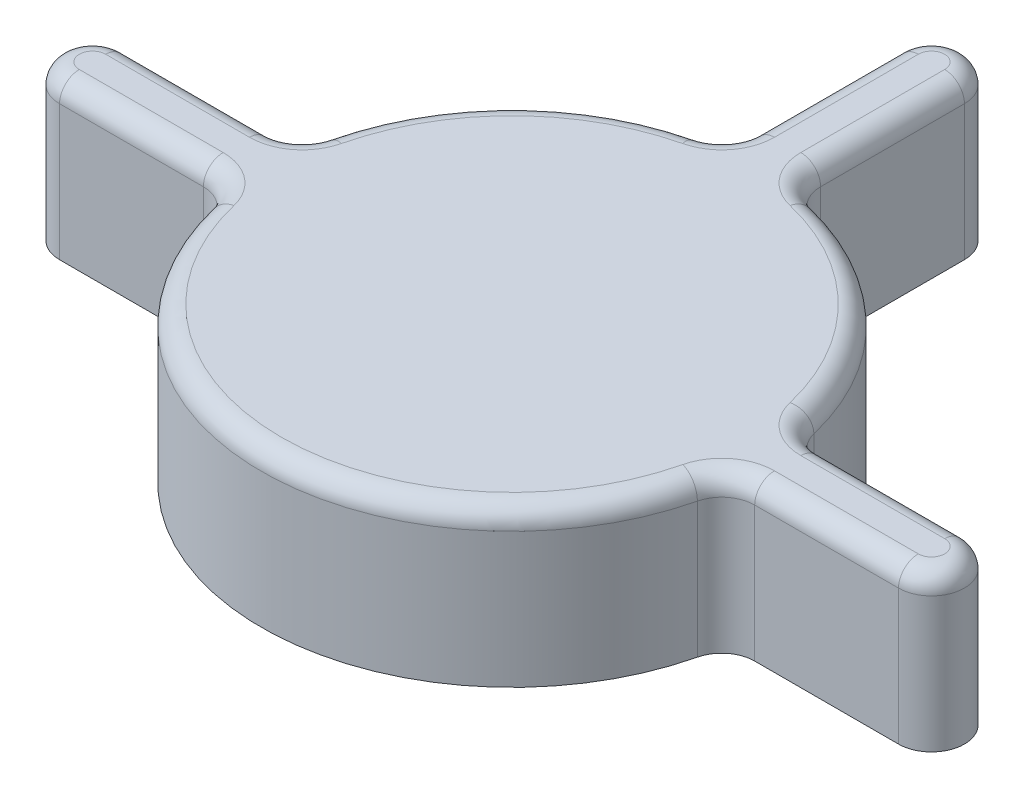
SolidWorks part; units mm, degrees
material "ABS PC"
ref_plane "Plan de face" through (0, 0, 0) normal (0, 0, 1) x (1, 0, 0)
ref_plane "Plan de dessus" through (0, 0, 0) normal (0, 1, 0) x (1, 0, 0)
ref_plane "Plan de droite" through (0, 0, 0) normal (1, 0, 0) x (0, 0, -1)
sketch "Esquisse1" plane through (0, 0, 0) normal (0, 1, 0) x (1, 0, 0)
  line L8 (15.5, -48.7904) -> (15.5, -37.7988)
  line L9 (41.821, -5) -> (63.6396, -5)
  line L10 (63.6396, 5) -> (41.821, 5)
  line L11 (5, 41.821) -> (5, 63.6396)
  line L12 (-5, 63.6396) -> (-5, 41.821)
  line L13 (-41.821, 5) -> (-63.6396, 5)
  line L14 (-63.6396, -5) -> (-41.821, -5)
  line L15 (-15.5, -37.7988) -> (-15.5, -48.7904)
  line L17 (41.821, -5) -> (63.6396, -5)
  line L18 (63.6396, 5) -> (41.821, 5)
  line L19 (5, 41.821) -> (5, 63.6396)
  line L20 (-5, 63.6396) -> (-5, 41.821)
  line L21 (-41.821, 5) -> (-63.6396, 5)
  line L22 (-63.6396, -5) -> (-41.821, -5)
  arc A16 (18.1163, -33.4036) -> (15.5, -37.7988) centre (20.5, -37.7988) ccw
  arc A17 (18.1163, -33.4036) -> (36.9581, -8.8372) centre (0, 0) ccw
  arc A18 (41.821, -5) -> (36.9581, -8.8372) centre (41.821, -10) ccw
  arc A19 (63.6396, -5) -> (63.6396, 5) centre (63.6396, 0) ccw
  arc A20 (36.9581, 8.8372) -> (41.821, 5) centre (41.821, 10) ccw
  arc A21 (36.9581, 8.8372) -> (8.8372, 36.9581) centre (0, 0) ccw
  arc A22 (5, 41.821) -> (8.8372, 36.9581) centre (10, 41.821) ccw
  arc A23 (5, 63.6396) -> (-5, 63.6396) centre (0, 63.6396) ccw
  arc A24 (-8.8372, 36.9581) -> (-5, 41.821) centre (-10, 41.821) ccw
  arc A25 (-8.8372, 36.9581) -> (-36.9581, 8.8372) centre (0, 0) ccw
  arc A26 (-41.821, 5) -> (-36.9581, 8.8372) centre (-41.821, 10) ccw
  arc A27 (-63.6396, 5) -> (-63.6396, -5) centre (-63.6396, 0) ccw
  arc A28 (-36.9581, -8.8372) -> (-41.821, -5) centre (-41.821, -10) ccw
  arc A29 (-36.9581, -8.8372) -> (-18.1163, -33.4036) centre (0, 0) ccw
  arc A30 (-15.5, -37.7988) -> (-18.1163, -33.4036) centre (-20.5, -37.7988) ccw
  arc A31 (-15.5, -48.7904) -> (15.5, -48.7904) centre (0, -48.7904) ccw
  arc A33 (-18.1163, -33.4036) -> (36.9581, -8.8372) centre (0, 0) ccw
  arc A34 (41.821, -5) -> (36.9581, -8.8372) centre (41.821, -10) ccw
  arc A35 (63.6396, -5) -> (63.6396, 5) centre (63.6396, 0) ccw
  arc A36 (36.9581, 8.8372) -> (41.821, 5) centre (41.821, 10) ccw
  arc A37 (36.9581, 8.8372) -> (8.8372, 36.9581) centre (0, 0) ccw
  arc A38 (5, 41.821) -> (8.8372, 36.9581) centre (10, 41.821) ccw
  arc A39 (5, 63.6396) -> (-5, 63.6396) centre (0, 63.6396) ccw
  arc A40 (-8.8372, 36.9581) -> (-5, 41.821) centre (-10, 41.821) ccw
  arc A41 (-8.8372, 36.9581) -> (-36.9581, 8.8372) centre (0, 0) ccw
  arc A42 (-41.821, 5) -> (-36.9581, 8.8372) centre (-41.821, 10) ccw
  arc A43 (-63.6396, 5) -> (-63.6396, -5) centre (-63.6396, 0) ccw
  arc A44 (-36.9581, -8.8372) -> (-41.821, -5) centre (-41.821, -10) ccw
  arc A45 (-36.9581, -8.8372) -> (-18.1163, -33.4036) centre (0, 0) ccw
  point P3 (-17.4675, -33.4036)
  dimension "D1" = 0
extrude "Boss.-Extru.1" add sketch "Esquisse1" against normal offset from surface (23.5 mm away) 5
sketch "Esquisse2" plane through (0, -23.5, 0) normal (0, -1, 0) x (1, 0, 0)
  line L1 (45, 0.7) -> (65.7107, 0.7) construction
  line L2 (65.7107, -0.7) -> (45, -0.7) construction
  line L3 (45, 0.7) -> (65.7107, 0.7)
  line L4 (65.7107, -0.7) -> (45, -0.7)
  line L5 (65.7107, 0.7) -> (65.7107, -0.7) construction
  line L6 (65.7107, 0.7) -> (65.7107, -0.7)
  line L7 (45, -0.7) -> (45, 0.7) construction
  line L8 (45, -0.7) -> (45, 0.7)
  line L9 (0.7, -65.7107) -> (-0.7, -65.7107) construction
  line L10 (0.7, -65.7107) -> (-0.7, -65.7107)
  line L11 (-0.7, -45) -> (0.7, -45) construction
  line L12 (-0.7, -65.7107) -> (-0.7, -45) construction
  line L13 (0.7, -45) -> (0.7, -65.7107) construction
  line L14 (-0.7, -45) -> (0.7, -45)
  line L15 (-0.7, -65.7107) -> (-0.7, -45)
  line L16 (0.7, -45) -> (0.7, -65.7107)
  line L17 (-45, 0.7) -> (-45, -0.7) construction
  line L18 (-45, -0.7) -> (-65.7107, -0.7) construction
  line L19 (-65.7107, -0.7) -> (-65.7107, 0.7) construction
  line L20 (-45, 0.7) -> (-45, -0.7)
  line L21 (-45, -0.7) -> (-65.7107, -0.7)
  line L22 (-65.7107, -0.7) -> (-65.7107, 0.7)
  line L23 (-65.7107, 0.7) -> (-45, 0.7) construction
  line L24 (-65.7107, 0.7) -> (-45, 0.7)
extrude "Enlèv. mat.-Extru.1" cut sketch "Esquisse2" against normal blind 15
sketch "Esquisse3" plane through (0, -23.5, 0) normal (0, -1, 0) x (1, 0, 0)
  circle A0 centre (0, 0) radius 35
  arc A1 (8.8372, -36.9581) -> (36.9581, -8.8372) centre (0, 0) ccw construction
  dimension "D1" = 3
extrude "Enlèv. mat.-Extru.2" cut sketch "Esquisse3" against normal offset from surface (20.5 mm away) 3 up to face at (0, 0, -14.8493)
chamfer "Chanfrein1" distance 4 angle 45 1 edges at (0, -3, 35)
fillet "Congé1" radius 3 18 edges at (0, 0, 38) (-38.7238, 0, 6.0748) (-52.7303, 0, 5) (-68.6396, 0, 0) (-52.7303, 0, -5) (-38.7238, 0, -6.0748) (-26.8701, 0, -26.8701) (-6.0748, 0, -38.7238) (-5, 0, -52.7303) (0, 0, -68.6396) (5, 0, -52.7303) (6.0748, 0, -38.7238) (26.8701, 0, -26.8701) (38.7238, 0, -6.0748) (52.7303, 0, -5) (68.6396, 0, 0) (52.7303, 0, 5) (38.7238, 0, 6.0748)
